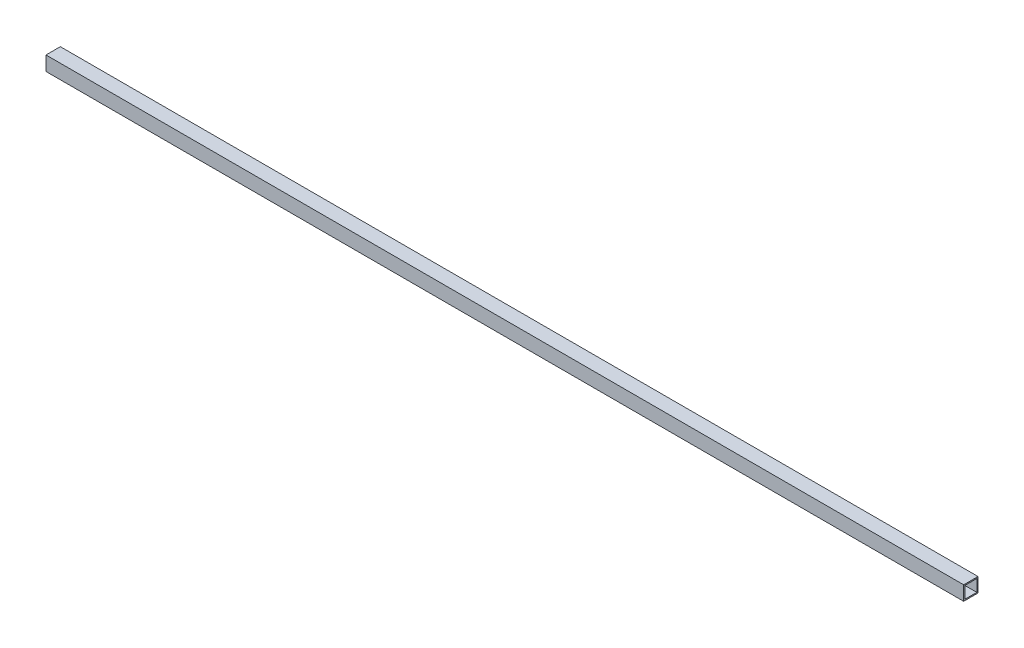
SolidWorks part; units mm, degrees
ref_plane "Front Plane" through (0, 0, 0) normal (0, 0, 1) x (1, 0, 0)
ref_plane "Top Plane" through (0, 0, 0) normal (0, 1, 0) x (1, 0, 0)
ref_plane "Right Plane" through (0, 0, 0) normal (1, 0, 0) x (0, 0, -1)
sketch "Sketch1" plane through (0, 0, 0) normal (1, 0, 0) x (0, 0, -1)
  line L0 (7.9375, -7.9375) -> (7.9375, 7.9375)
  line L1 (-9.525, -9.525) -> (9.525, -9.525)
  line L2 (-9.525, -9.525) -> (-9.525, 9.525)
  line L3 (-9.525, 9.525) -> (9.525, 9.525)
  line L4 (9.525, -9.525) -> (9.525, 9.525)
  line L5 (-9.525, -9.525) -> (9.525, 9.525) construction
  line L6 (-9.525, 9.525) -> (9.525, -9.525) construction
  line L7 (-7.9375, 7.9375) -> (7.9375, 7.9375)
  line L8 (-7.9375, -7.9375) -> (-7.9375, 7.9375)
  line L9 (-7.9375, -7.9375) -> (7.9375, -7.9375)
  point P0 (0, 0)
  dimension "D1" = 19.05
  dimension "D2" = 19.05
  dimension "D3" = 1.5875
extrude "Boss-Extrude1" add sketch "Sketch1" along normal blind 1219.2
